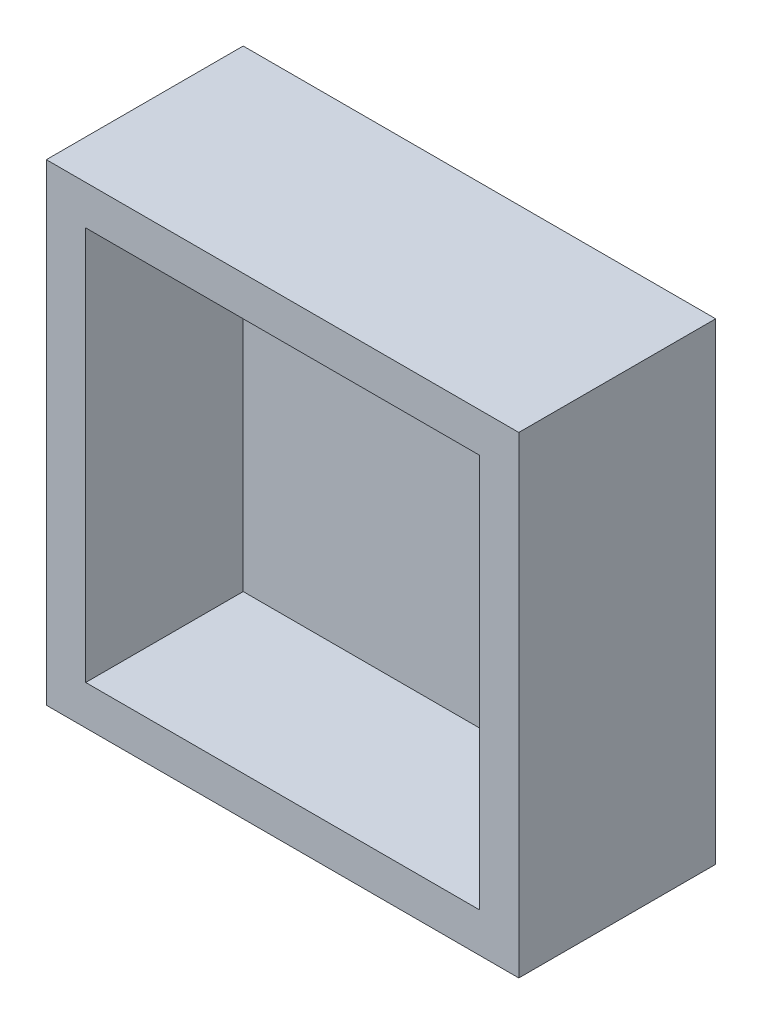
SolidWorks part; units mm, degrees
ref_plane "前视基准面" through (0, 0, 0) normal (0, 0, 1) x (1, 0, 0)
ref_plane "上视基准面" through (0, 0, 0) normal (0, 1, 0) x (1, 0, 0)
ref_plane "右视基准面" through (0, 0, 0) normal (1, 0, 0) x (0, 0, -1)
other "Configuration Table"
sketch "草图1" plane through (0, 0, 0) normal (0, 0, 1) x (1, 0, 0)
  line L1 (-10, 10) -> (10, 10)
  line L2 (-10, 10) -> (-10, -10)
  line L3 (-10, -10) -> (10, -10)
  line L4 (10, 10) -> (10, -10)
  line L5 (-10, 10) -> (10, -10) construction
  line L6 (-10, -10) -> (10, 10) construction
  point P0 (0, 0)
extrude "凸台-拉伸1" add sketch "草图1" along normal blind 2
sketch "草图2" plane through (0, -10, 0) normal (0, -1, 0) x (1, 0, 0)
  line L0 (-10, 0) -> (-10, 10)
  line L1 (-10, 0) -> (10, 0)
  line L2 (10, 0) -> (10, 10)
  line L3 (10, 10) -> (-10, 10)
extrude "凸台-拉伸3" add sketch "草图2" along normal blind 2
sketch "草图4" plane through (0, 10, 0) normal (0, 1, 0) x (1, 0, 0)
  line L0 (-10, 0) -> (-10, -10)
  line L1 (-10, -10) -> (10, -10)
  line L2 (10, -10) -> (10, 0)
  line L3 (10, 0) -> (-10, 0)
extrude "凸台-拉伸4" add sketch "草图4" along normal blind 2
sketch "草图5" plane through (10, 0, 0) normal (1, 0, 0) x (0, 0, -1)
  line L0 (-10, 12) -> (0, 12)
  line L1 (0, 12) -> (0, -12)
  line L2 (0, -12) -> (-10, -12)
  line L3 (-10, -12) -> (-10, 12)
extrude "凸台-拉伸5" add sketch "草图5" along normal blind 2
sketch "草图6" plane through (-10, 0, 0) normal (-1, 0, 0) x (0, 0, 1)
  line L0 (0, 12) -> (10, 12)
  line L1 (10, 12) -> (10, -12)
  line L2 (10, -12) -> (0, -12) construction
  line L3 (10, -12) -> (10, -10) construction
  line L4 (10, -12) -> (0, -12)
  line L5 (0, -12) -> (0, 12)
extrude "凸台-拉伸6" add sketch "草图6" along normal blind 2
